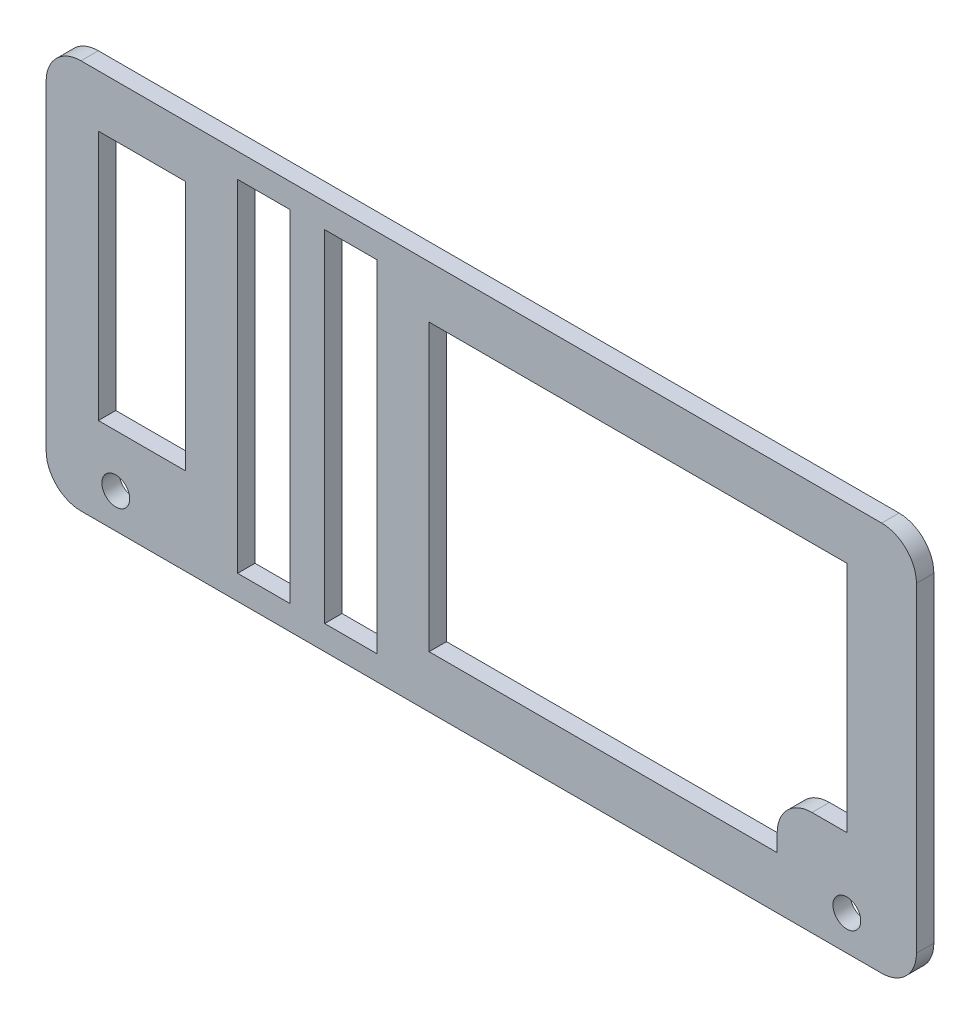
SolidWorks part; units mm, degrees
material "1060 Alloy"
ref_plane "Front Plane" through (0, 0, 0) normal (0, 0, 1) x (1, 0, 0)
ref_plane "Top Plane" through (0, 0, 0) normal (0, 1, 0) x (1, 0, 0)
ref_plane "Right Plane" through (0, 0, 0) normal (1, 0, 0) x (0, 0, -1)
sketch "Sketch1" plane through (0, 0, 0) normal (0, 0, 1) x (1, 0, 0)
  line L1 (-182.6642, 87.9124) -> (67.3358, 87.9124)
  line L2 (-182.6642, 87.9124) -> (-182.6642, -24.0876)
  line L3 (-182.6642, -24.0876) -> (67.3358, -24.0876)
  line L4 (67.3358, 87.9124) -> (67.3358, -24.0876)
  line L5 (-182.6642, 87.9124) -> (67.3358, -24.0876) construction
  line L6 (-182.6642, -24.0876) -> (67.3358, 87.9124) construction
  point P0 (-57.6642, 31.9124)
  dimension "D1" = 250
  dimension "D2" = 112
extrude "Boss-Extrude1" add sketch "Sketch1" along normal blind 5 contours L1 L4 L3 L2
sketch "Sketch2" plane through (0, 0, 5) normal (0, 0, 1) x (1, 0, 0)
  line L1 (-182.6642, -24.0876) -> (67.3358, -24.0876) construction
  line L2 (67.3358, 87.9124) -> (67.3358, -24.0876) construction
  circle A0 centre (-162.6642, -14.0876) radius 4
  dimension "D1" = 8
  dimension "D2" = 230
  dimension "D3" = 10
extrude "Cut-Extrude1" cut sketch "Sketch2" against normal blind 11
sketch "Sketch3" plane through (0, 0, 5) normal (0, 0, 1) x (1, 0, 0)
  line L0 (67.3358, 87.9124) -> (67.3358, -24.0876) construction
  line L1 (-182.6642, -24.0876) -> (67.3358, -24.0876) construction
  circle A0 centre (47.3358, -14.0876) radius 4
  dimension "D1" = 8
  dimension "D2" = 20
  dimension "D3" = 10
extrude "Cut-Extrude2" cut sketch "Sketch3" against normal blind 15
sketch "Sketch4" plane through (0, 0, 5) normal (0, 0, 1) x (1, 0, 0)
  line L0 (-127.6642, 80.9124) -> (-127.6642, -17.0876)
  line L1 (-127.6642, -17.0876) -> (-112.6642, -17.0876)
  line L3 (-182.6642, -24.0876) -> (67.3358, -24.0876) construction
  line L4 (-102.6642, -17.0876) -> (-102.6642, 80.9124)
  line L5 (-87.6642, -17.0876) -> (-87.6642, 80.9124)
  line L6 (-87.6642, -17.0876) -> (-102.6642, -17.0876)
  line L7 (-102.6642, 80.9124) -> (-87.6642, 80.9124)
  line L8 (-182.6642, 87.9124) -> (67.3358, 87.9124) construction
  line L9 (-112.6642, 138.0091) -> (-112.6642, -44.1468) construction
  line L10 (-112.6642, 80.9124) -> (-112.6642, -17.0876)
  line L11 (-112.6642, 80.9124) -> (-127.6642, 80.9124)
  line L12 (-182.6642, 87.9124) -> (-182.6642, -24.0876) construction
  dimension "D1" = 7
  dimension "D2" = 55
  dimension "D3" = 15
  dimension "D4" = 7
  dimension "D5" = 80
  dimension "D8" = 7
  dimension "D9" = 15
extrude "Cut-Extrude4" cut sketch "Sketch4" against normal blind 15
sketch "Sketch5" plane through (0, 0, 5) normal (0, 0, 1) x (1, 0, 0)
  line L1 (17.3977, 72.9124) -> (-72.6642, 72.9124)
  line L2 (17.3977, 72.9124) -> (47.3358, 72.9124)
  line L3 (27.3358, -9.0876) -> (-72.6642, -9.0876)
  line L4 (-72.6642, 72.9124) -> (-72.6642, -9.0876)
  line L5 (-182.6642, 87.9124) -> (67.3358, 87.9124) construction
  line L6 (-182.6642, -24.0876) -> (67.3358, -24.0876) construction
  line L7 (47.3358, 72.9124) -> (47.3358, 5.9124)
  line L8 (47.3358, 5.9124) -> (27.3358, 5.9124)
  line L9 (27.3358, 5.9124) -> (27.3358, -9.0876)
  line L10 (67.3358, 87.9124) -> (67.3358, -24.0876) construction
  line L11 (-87.6642, -17.0876) -> (-87.6642, 80.9124) construction
  circle A0 centre (47.3358, -14.0876) radius 4 construction
  dimension "D5" = 20
  dimension "D6" = 20
  dimension "D1" = 15
  dimension "D2" = 15
  dimension "D3" = 15
  dimension "D4" = 20
extrude "Cut-Extrude5" cut sketch "Sketch5" against normal blind 15
fillet "Fillet1" radius 10 5 edges at (-182.6642, -24.0876, 2.5) (27.3358, 5.9124, 2.5) (67.3358, -24.0876, 2.5) (67.3358, 87.9124, 2.5) (-182.6642, 87.9124, 2.5)
sketch "Sketch6" plane through (0, 0, 5) normal (0, 0, 1) x (1, 0, 0)
  line L0 (-142.6642, 72.9124) -> (-142.6642, 0.9124)
  line L1 (-142.6642, 0.9124) -> (-167.6642, 0.9124)
  line L2 (-167.6642, 0.9124) -> (-167.6642, 72.9124)
  line L3 (-167.6642, 72.9124) -> (-142.6642, 72.9124)
  line L4 (-127.6642, 80.9124) -> (-127.6642, -17.0876) construction
  line L5 (-182.6642, 77.9124) -> (-182.6642, -14.0876) construction
  line L6 (-172.6642, 87.9124) -> (57.3358, 87.9124) construction
  circle A0 centre (-162.6642, -14.0876) radius 4 construction
  dimension "D1" = 15
  dimension "D2" = 15
  dimension "D3" = 15
  dimension "D4" = 15
extrude "Cut-Extrude6" cut sketch "Sketch6" against normal blind 5
